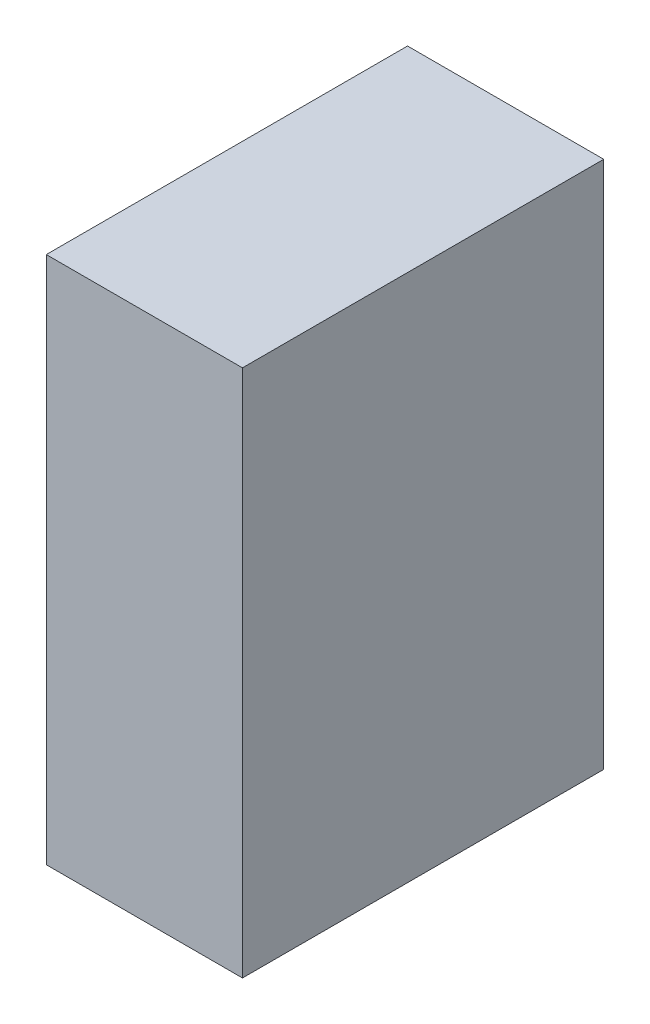
SolidWorks part; units mm, degrees
ref_plane "Front Plane" through (0, 0, 0) normal (0, 0, 1) x (1, 0, 0)
ref_plane "Top Plane" through (0, 0, 0) normal (0, 1, 0) x (1, 0, 0)
ref_plane "Right Plane" through (0, 0, 0) normal (1, 0, 0) x (0, 0, -1)
sketch "Sketch1" plane through (0, 0, 0) normal (0, 1, 0) x (1, 0, 0)
  line L1 (-36.2434, -1.6637) -> (-15.8234, -1.6637)
  line L2 (-36.2434, -1.6637) -> (-36.2434, -39.2637)
  line L3 (-36.2434, -39.2637) -> (-15.8234, -39.2637)
  line L4 (-15.8234, -1.6637) -> (-15.8234, -39.2637)
extrude "Boss-Extrude1" add sketch "Sketch1" along normal blind 55
